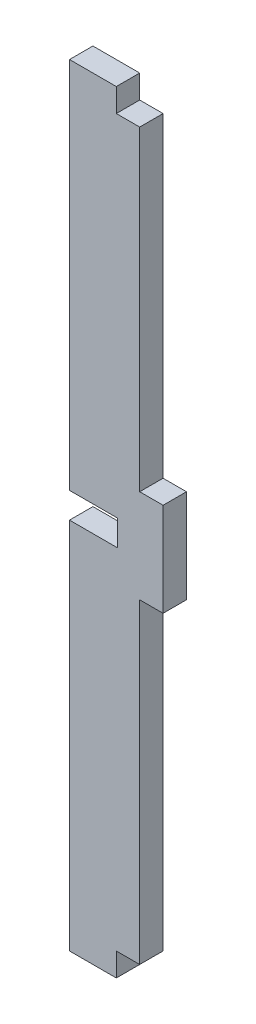
SolidWorks part; units mm, degrees
ref_plane "Front Plane" through (0, 0, 0) normal (0, 0, 1) x (1, 0, 0)
ref_plane "Top Plane" through (0, 0, 0) normal (0, 1, 0) x (1, 0, 0)
ref_plane "Right Plane" through (0, 0, 0) normal (1, 0, 0) x (0, 0, -1)
sketch "Model" plane through (0, 0, 0) normal (0, 0, 1) x (1, 0, 0)
  line L0 (-336.4543, -134.1912) -> (-336.4543, -213.9412)
  line L1 (-321.4543, -208.9412) -> (-321.4543, -141.4412)
  line L2 (-326.4543, -48.9412) -> (-336.4543, -48.9412)
  line L3 (-326.4543, -208.9412) -> (-321.4543, -208.9412)
  line L4 (-336.4543, -213.9412) -> (-326.4543, -213.9412)
  line L5 (-326.4543, -213.9412) -> (-326.4543, -208.9412)
  line L6 (-321.4543, -141.4412) -> (-316.4543, -141.4412)
  line L7 (-316.4543, -141.4412) -> (-316.4543, -121.4412)
  line L8 (-316.4543, -121.4412) -> (-321.4543, -121.4412)
  line L9 (-321.4543, -121.4412) -> (-321.4543, -53.9412)
  line L10 (-321.4543, -53.9412) -> (-326.4543, -53.9412)
  line L11 (-326.4543, -53.9412) -> (-326.4543, -48.9412)
  line L12 (-336.4543, -48.9412) -> (-336.4543, -128.6912)
  line L13 (-326.2043, -128.6912) -> (-336.4543, -128.6912)
  line L14 (-326.2043, -134.1912) -> (-326.2043, -128.6912)
  line L15 (-336.4543, -134.1912) -> (-326.2043, -134.1912)
  line L16 (-318.4543, -138.0497) -> (-320.6522, -138.0497)
  line L17 (-320.5835, -136.4747) -> (-320.4773, -136.1391)
  line L18 (-320.4773, -136.1391) -> (-320.3431, -135.9658)
  line L19 (-320.3431, -135.9658) -> (-320.1901, -135.9081)
  line L20 (-320.1901, -135.9081) -> (-318.9351, -135.9081)
  line L21 (-318.9351, -135.9081) -> (-318.8364, -135.9287)
  line L22 (-318.8364, -135.9287) -> (-318.7462, -135.9908)
  line L23 (-318.7462, -135.9908) -> (-318.5917, -136.239)
  line L24 (-318.5917, -136.239) -> (-318.4887, -136.5996)
  line L25 (-318.4887, -136.5996) -> (-318.4543, -137.032)
  line L26 (-318.4543, -137.032) -> (-318.4543, -138.0497)
  line L27 (-322.7623, -138.0497) -> (-318.4543, -138.0497)
  line L28 (-318.4543, -138.0497) -> (-318.4543, -137.032)
  line L29 (-318.4543, -137.032) -> (-318.4887, -136.5996)
  line L30 (-318.4887, -136.5996) -> (-318.5917, -136.239)
  line L31 (-318.5917, -136.239) -> (-318.7462, -135.9908)
  line L32 (-318.7462, -135.9908) -> (-318.8364, -135.9287)
  line L33 (-318.8364, -135.9287) -> (-318.9351, -135.9081)
  line L34 (-318.9351, -135.9081) -> (-320.19, -135.9081)
  line L35 (-320.19, -135.9081) -> (-320.3429, -135.9658)
  line L36 (-320.3429, -135.9658) -> (-320.4772, -136.1391)
  line L37 (-320.4772, -136.1391) -> (-320.5835, -136.4747)
  line L38 (-320.5835, -136.4747) -> (-320.6522, -137.032)
  line L39 (-320.716, -136.481) -> (-320.8206, -136.1391)
  line L40 (-320.8206, -136.1391) -> (-320.9595, -135.9658)
  line L41 (-320.9595, -135.9658) -> (-321.114, -135.9081)
  line L42 (-321.114, -135.9081) -> (-322.2815, -135.9081)
  line L43 (-322.2815, -135.9081) -> (-322.3752, -135.9287)
  line L44 (-322.3752, -135.9287) -> (-322.4626, -135.9908)
  line L45 (-322.4626, -135.9908) -> (-322.6187, -136.239)
  line L46 (-322.6187, -136.239) -> (-322.7264, -136.6027)
  line L47 (-322.7264, -136.6027) -> (-322.7623, -137.032)
  line L48 (-322.7623, -137.032) -> (-322.7623, -138.0497)
  line L49 (-320.6522, -137.032) -> (-320.6522, -138.0497)
  line L50 (-320.6522, -138.0497) -> (-322.7623, -138.0497)
  line L51 (-322.7623, -138.0497) -> (-322.7623, -137.032)
  line L52 (-322.7623, -137.032) -> (-322.7264, -136.6027)
  line L53 (-322.7264, -136.6027) -> (-322.6186, -136.239)
  line L54 (-322.6186, -136.239) -> (-322.4625, -135.9908)
  line L55 (-322.4625, -135.9908) -> (-322.3751, -135.9287)
  line L56 (-322.3751, -135.9287) -> (-322.2815, -135.9081)
  line L57 (-322.2815, -135.9081) -> (-321.1139, -135.9081)
  line L58 (-321.1139, -135.9081) -> (-320.9593, -135.9658)
  line L59 (-320.9593, -135.9658) -> (-320.8204, -136.1391)
  line L60 (-320.8204, -136.1391) -> (-320.716, -136.481)
  line L61 (-320.716, -136.481) -> (-320.6522, -137.032)
  line L62 (-322.7684, -133.9913) -> (-320.6518, -133.4396)
  line L63 (-322.7684, -133.9913) -> (-320.6519, -134.5121)
  line L64 (-320.2713, -133.3419) -> (-318.4543, -132.8674)
  line L65 (-318.4895, -131.3729) -> (-318.5948, -131.7343)
  line L66 (-318.5948, -131.7343) -> (-318.7501, -131.9754)
  line L67 (-318.7501, -131.9754) -> (-318.8389, -132.0357)
  line L68 (-318.8389, -132.0357) -> (-318.9351, -132.0558)
  line L69 (-318.9351, -132.0558) -> (-318.8389, -132.0357)
  line L70 (-318.8389, -132.0357) -> (-318.7501, -131.9754)
  line L71 (-318.7501, -131.9754) -> (-318.5948, -131.7343)
  line L72 (-318.5948, -131.7343) -> (-318.4895, -131.3729)
  line L73 (-318.4895, -130.4909) -> (-318.5948, -130.1296)
  line L74 (-318.5948, -130.1296) -> (-318.7501, -129.8884)
  line L75 (-318.7501, -129.8884) -> (-318.8389, -129.8281)
  line L76 (-318.8389, -129.8281) -> (-318.9351, -129.808)
  line L77 (-318.9351, -129.808) -> (-320.6457, -129.808)
  line L78 (-320.6457, -129.808) -> (-320.742, -129.8281)
  line L79 (-320.742, -129.8281) -> (-320.8307, -129.8884)
  line L80 (-320.8307, -129.8884) -> (-320.9861, -130.1296)
  line L81 (-320.9861, -130.1296) -> (-321.0914, -130.4909)
  line L82 (-321.0914, -130.4909) -> (-321.1265, -130.9319)
  line L83 (-321.1265, -130.9319) -> (-321.0266, -131.6063)
  line L84 (-321.0266, -131.6063) -> (-320.9002, -131.8373)
  line L85 (-320.9002, -131.8373) -> (-320.6457, -132.0558)
  line L86 (-320.6457, -132.0558) -> (-322.7623, -132.0558)
  line L87 (-322.7623, -132.0558) -> (-322.7623, -129.883)
  line L88 (-322.7623, -129.883) -> (-322.7623, -132.0558)
  line L89 (-322.7623, -132.0558) -> (-320.6457, -132.0558)
  line L90 (-320.6457, -132.0558) -> (-320.9002, -131.8373)
  line L91 (-320.9002, -131.8373) -> (-321.0266, -131.6063)
  line L92 (-321.0266, -131.6063) -> (-321.1265, -130.9319)
  line L93 (-321.1265, -130.9319) -> (-321.0914, -130.4909)
  line L94 (-321.0914, -130.4909) -> (-320.9861, -130.1296)
  line L95 (-320.9861, -130.1296) -> (-320.8307, -129.8884)
  line L96 (-320.8307, -129.8884) -> (-320.742, -129.8281)
  line L97 (-320.742, -129.8281) -> (-320.6457, -129.808)
  line L98 (-320.6457, -129.808) -> (-318.9351, -129.808)
  line L99 (-318.9351, -129.808) -> (-318.8389, -129.8281)
  line L100 (-318.8389, -129.8281) -> (-318.7501, -129.8884)
  line L101 (-318.7501, -129.8884) -> (-318.5948, -130.1296)
  line L102 (-318.5948, -130.1296) -> (-318.4895, -130.4909)
  line L103 (-318.4895, -130.4909) -> (-318.4543, -130.9319)
  line L104 (-318.4543, -130.9319) -> (-318.4895, -131.3729)
  line L105 (-320.6518, -133.4396) -> (-320.277, -133.3419)
  line L106 (-320.6519, -134.5121) -> (-318.4543, -135.0528)
  line L107 (-320.6519, -134.5121) -> (-320.6518, -133.4396)
  line L108 (-323.4543, -126.308) -> (-318.4543, -126.308)
  line L109 (-320.4543, -127.308) -> (-318.4543, -126.308)
  line L110 (-320.4543, -125.308) -> (-318.4543, -126.308)
  line L111 (-323.9543, -95.9329) -> (-323.9543, -79.4495)
  line L112 (-329.35, -93.8973) -> (-329.35, -95.9329)
  line L113 (-333.5702, -89.939) -> (-329.35, -89.939)
  line L114 (-325.5382, -91.815) -> (-325.7185, -91.6909)
  line L115 (-325.5382, -91.815) -> (-325.229, -92.3114)
  line L116 (-325.2291, -86.3175) -> (-325.5382, -85.8211)
  line L117 (-329.0004, -92.1116) -> (-329.2127, -92.7828)
  line L118 (-332.6087, -91.6495) -> (-330.2737, -91.6495)
  line L119 (-329.35, -95.9329) -> (-324.9543, -95.9329)
  line L120 (-325.2291, -86.3175) -> (-325.023, -87.0387)
  line L121 (-325.7185, -85.697) -> (-325.9159, -85.6556)
  line L122 (-333.4984, -93.0388) -> (-333.5702, -93.8973)
  line L123 (-325.9159, -91.6495) -> (-328.4259, -91.6495)
  line L124 (-328.4257, -85.6556) -> (-325.9159, -85.6556)
  line L125 (-324.9543, -93.8973) -> (-324.9543, -95.9329)
  line L126 (-328.7319, -91.7651) -> (-329.0004, -92.1116)
  line L127 (-329.2127, -92.7828) -> (-329.35, -93.8973)
  line L128 (-324.9543, -93.8973) -> (-325.023, -93.0326)
  line L129 (-328.7315, -85.7712) -> (-328.4257, -85.6556)
  line L130 (-329.6868, -92.1116) -> (-329.4776, -92.7953)
  line L131 (-325.023, -87.0387) -> (-324.9543, -87.9034)
  line L132 (-329.9643, -91.7651) -> (-330.2737, -91.6495)
  line L133 (-325.023, -93.0326) -> (-325.229, -92.3114)
  line L134 (-332.6087, -91.6495) -> (-332.796, -91.6909)
  line L135 (-332.9708, -91.815) -> (-333.2829, -92.3114)
  line L136 (-324.9543, -87.9034) -> (-324.9543, -89.939)
  line L137 (-325.5382, -85.8211) -> (-325.7185, -85.697)
  line L138 (-329.0004, -86.1177) -> (-329.2127, -86.7889)
  line L139 (-329.6868, -92.1116) -> (-329.9643, -91.7651)
  line L140 (-329.0004, -86.1177) -> (-328.7315, -85.7712)
  line L141 (-333.5702, -95.9329) -> (-333.5702, -93.8973)
  line L142 (-333.5702, -95.9329) -> (-329.35, -95.9329)
  line L143 (-333.4984, -93.0388) -> (-333.2829, -92.3114)
  line L144 (-332.9708, -91.815) -> (-332.796, -91.6909)
  line L145 (-328.4259, -91.6495) -> (-328.7319, -91.7651)
  line L146 (-325.7185, -91.6909) -> (-325.9159, -91.6495)
  line L147 (-329.35, -93.8973) -> (-329.4776, -92.7953)
  line L148 (-329.2127, -86.7889) -> (-329.35, -87.9034)
  line L149 (-333.5702, -83.9451) -> (-329.3372, -83.9451)
  line L150 (-330.2988, -81.6973) -> (-330.2285, -80.8153)
  line L151 (-329.3372, -79.4495) -> (-325.9158, -79.4495)
  line L152 (-329.3372, -79.4495) -> (-329.5296, -79.4896)
  line L153 (-324.9543, -81.6973) -> (-325.0246, -82.5792)
  line L154 (-329.5296, -79.4896) -> (-329.7072, -79.6102)
  line L155 (-333.5702, -83.9451) -> (-333.5702, -79.5993)
  line L156 (-333.5702, -87.9034) -> (-333.5702, -89.939)
  line L157 (-329.35, -87.9034) -> (-329.35, -89.939)
  line L158 (-329.7072, -79.6102) -> (-330.0178, -80.0926)
  line L159 (-330.2988, -81.6973) -> (-330.0989, -83.046)
  line L160 (-332.7959, -85.697) -> (-332.9708, -85.8211)
  line L161 (-329.3372, -83.9451) -> (-329.846, -83.508)
  line L162 (-330.2285, -80.8153) -> (-330.0178, -80.0926)
  line L163 (-325.2353, -83.302) -> (-325.5459, -83.7843)
  line L164 (-325.9158, -79.4495) -> (-325.7235, -79.4896)
  line L165 (-333.4984, -87.0449) -> (-333.5702, -87.9034)
  line L166 (-325.7235, -79.4896) -> (-325.5459, -79.6102)
  line L167 (-325.5459, -79.6102) -> (-325.2353, -80.0926)
  line L168 (-329.6868, -86.1177) -> (-329.4776, -86.8014)
  line L169 (-330.0989, -83.046) -> (-329.846, -83.508)
  line L170 (-325.2353, -83.302) -> (-325.0246, -82.5792)
  line L171 (-332.6087, -85.6556) -> (-330.2737, -85.6556)
  line L172 (-332.6087, -85.6556) -> (-332.7959, -85.697)
  line L173 (-333.283, -86.3175) -> (-332.9708, -85.8211)
  line L174 (-330.2737, -85.6556) -> (-329.9643, -85.7712)
  line L175 (-329.4776, -86.8014) -> (-329.35, -87.9034)
  line L176 (-329.6868, -86.1177) -> (-329.9643, -85.7712)
  line L177 (-333.4984, -87.0449) -> (-333.283, -86.3175)
  line L178 (-325.9158, -83.9451) -> (-325.7235, -83.9049)
  line L179 (-325.7235, -83.9049) -> (-325.5459, -83.7843)
  line L180 (-325.2353, -80.0926) -> (-325.0246, -80.8153)
  line L181 (-325.0246, -80.8153) -> (-324.9543, -81.6973)
  line L182 (-329.35, -89.939) -> (-324.9543, -89.939)
  line L183 (-328.4543, -61.1859) -> (-330.6522, -61.1859)
  line L184 (-330.6522, -61.1859) -> (-330.6522, -60.1682)
  line L185 (-330.6522, -60.1682) -> (-330.5835, -59.6109)
  line L186 (-330.5835, -59.6109) -> (-330.4773, -59.2753)
  line L187 (-330.4773, -59.2753) -> (-330.3431, -59.102)
  line L188 (-330.3431, -59.102) -> (-330.1901, -59.0443)
  line L189 (-330.1901, -59.0443) -> (-328.9351, -59.0443)
  line L190 (-328.9351, -59.0443) -> (-328.8364, -59.0649)
  line L191 (-328.8364, -59.0649) -> (-328.7462, -59.127)
  line L192 (-328.7462, -59.127) -> (-328.5917, -59.3752)
  line L193 (-328.5917, -59.3752) -> (-328.4887, -59.7358)
  line L194 (-328.4887, -59.7358) -> (-328.4543, -60.1682)
  line L195 (-328.4543, -60.1682) -> (-328.4543, -61.1859)
  line L196 (-332.7623, -61.1859) -> (-328.4543, -61.1859)
  line L197 (-328.4543, -61.1859) -> (-328.4543, -60.1682)
  line L198 (-328.4543, -60.1682) -> (-328.4887, -59.7358)
  line L199 (-328.4887, -59.7358) -> (-328.5917, -59.3752)
  line L200 (-328.5917, -59.3752) -> (-328.7462, -59.127)
  line L201 (-328.7462, -59.127) -> (-328.8364, -59.0649)
  line L202 (-328.8364, -59.0649) -> (-328.9351, -59.0443)
  line L203 (-328.9351, -59.0443) -> (-330.19, -59.0443)
  line L204 (-330.19, -59.0443) -> (-330.3429, -59.102)
  line L205 (-330.3429, -59.102) -> (-330.4772, -59.2753)
  line L206 (-330.4772, -59.2753) -> (-330.5833, -59.6109)
  line L207 (-330.5833, -59.6109) -> (-330.652, -60.1682)
  line L208 (-330.652, -60.1682) -> (-330.716, -59.6172)
  line L209 (-330.716, -59.6172) -> (-330.8206, -59.2753)
  line L210 (-330.8206, -59.2753) -> (-330.9595, -59.102)
  line L211 (-330.9595, -59.102) -> (-331.114, -59.0443)
  line L212 (-331.114, -59.0443) -> (-332.2815, -59.0443)
  line L213 (-332.2815, -59.0443) -> (-332.3752, -59.0649)
  line L214 (-332.3752, -59.0649) -> (-332.4626, -59.127)
  line L215 (-332.4626, -59.127) -> (-332.6187, -59.3752)
  line L216 (-332.6187, -59.3752) -> (-332.7264, -59.7389)
  line L217 (-332.7264, -59.7389) -> (-332.7623, -60.1682)
  line L218 (-332.7623, -60.1682) -> (-332.7623, -61.1859)
  line L219 (-330.6518, -60.1682) -> (-330.6518, -61.1859)
  line L220 (-330.6518, -61.1859) -> (-332.7623, -61.1859)
  line L221 (-332.7623, -61.1859) -> (-332.7623, -60.1682)
  line L222 (-332.7623, -60.1682) -> (-332.7264, -59.7389)
  line L223 (-332.7264, -59.7389) -> (-332.6186, -59.3752)
  line L224 (-332.6186, -59.3752) -> (-332.4625, -59.127)
  line L225 (-332.4625, -59.127) -> (-332.3751, -59.0649)
  line L226 (-332.3751, -59.0649) -> (-332.2815, -59.0443)
  line L227 (-332.2815, -59.0443) -> (-331.1139, -59.0443)
  line L228 (-331.1139, -59.0443) -> (-330.9593, -59.102)
  line L229 (-330.9593, -59.102) -> (-330.8204, -59.2753)
  line L230 (-330.8204, -59.2753) -> (-330.7158, -59.6172)
  line L231 (-330.7158, -59.6172) -> (-330.6518, -60.1682)
  line L232 (-332.7684, -58.189) -> (-328.4543, -58.189)
  line L233 (-328.4543, -56.0651) -> (-328.4895, -56.5061)
  line L234 (-328.4895, -56.5061) -> (-328.5948, -56.8674)
  line L235 (-328.5948, -56.8674) -> (-328.7501, -57.1086)
  line L236 (-328.7501, -57.1086) -> (-328.8389, -57.1689)
  line L237 (-328.8389, -57.1689) -> (-328.9351, -57.189)
  line L238 (-328.9351, -57.189) -> (-328.8389, -57.1689)
  line L239 (-328.8389, -57.1689) -> (-328.7501, -57.1086)
  line L240 (-328.7501, -57.1086) -> (-328.5948, -56.8674)
  line L241 (-328.5948, -56.8674) -> (-328.4895, -56.5061)
  line L242 (-328.4895, -55.6241) -> (-328.5948, -55.2627)
  line L243 (-328.5948, -55.2627) -> (-328.7501, -55.0216)
  line L244 (-328.7501, -55.0216) -> (-328.8389, -54.9613)
  line L245 (-328.8389, -54.9613) -> (-328.9351, -54.9412)
  line L246 (-328.9351, -54.9412) -> (-330.6457, -54.9412)
  line L247 (-330.6457, -54.9412) -> (-330.742, -54.9613)
  line L248 (-330.742, -54.9613) -> (-330.8307, -55.0216)
  line L249 (-330.8307, -55.0216) -> (-330.9861, -55.2627)
  line L250 (-330.9861, -55.2627) -> (-331.0914, -55.6241)
  line L251 (-331.0914, -55.6241) -> (-331.1265, -56.0651)
  line L252 (-331.1265, -56.0651) -> (-331.0266, -56.7394)
  line L253 (-331.0266, -56.7394) -> (-330.9002, -56.9705)
  line L254 (-330.9002, -56.9705) -> (-330.6457, -57.189)
  line L255 (-330.6457, -57.189) -> (-332.7623, -57.189)
  line L256 (-332.7623, -57.189) -> (-332.7623, -55.0161)
  line L257 (-332.7623, -55.0161) -> (-332.7623, -57.189)
  line L258 (-332.7623, -57.189) -> (-330.6457, -57.189)
  line L259 (-330.6457, -57.189) -> (-330.9002, -56.9705)
  line L260 (-330.9002, -56.9705) -> (-331.0266, -56.7394)
  line L261 (-331.0266, -56.7394) -> (-331.1265, -56.0651)
  line L262 (-331.1265, -56.0651) -> (-331.0914, -55.6241)
  line L263 (-331.0914, -55.6241) -> (-330.9861, -55.2627)
  line L264 (-330.9861, -55.2627) -> (-330.8307, -55.0216)
  line L265 (-330.8307, -55.0216) -> (-330.742, -54.9613)
  line L266 (-330.742, -54.9613) -> (-330.6457, -54.9412)
  line L267 (-330.6457, -54.9412) -> (-328.9351, -54.9412)
  line L268 (-328.9351, -54.9412) -> (-328.8389, -54.9613)
  line L269 (-328.8389, -54.9613) -> (-328.7501, -55.0216)
  line L270 (-328.7501, -55.0216) -> (-328.5948, -55.2627)
  line L271 (-328.5948, -55.2627) -> (-328.4895, -55.6241)
  line L272 (-328.4895, -55.6241) -> (-328.4543, -56.0651)
  line L273 (-333.4543, -51.4412) -> (-328.4543, -51.4412)
  line L274 (-330.4543, -52.4412) -> (-328.4543, -51.4412)
  line L275 (-330.4543, -50.4412) -> (-328.4543, -51.4412)
  line L276 (-329.1319, -151.9268) -> (-331.3297, -151.9268)
  line L277 (-331.3297, -151.9268) -> (-331.3297, -150.909)
  line L278 (-331.3297, -150.909) -> (-331.2611, -150.3518)
  line L279 (-331.2611, -150.3518) -> (-331.1549, -150.0161)
  line L280 (-331.1549, -150.0161) -> (-331.0207, -149.8429)
  line L281 (-331.0207, -149.8429) -> (-330.8677, -149.7851)
  line L282 (-330.8677, -149.7851) -> (-329.6127, -149.7851)
  line L283 (-329.6127, -149.7851) -> (-329.5139, -149.8058)
  line L284 (-329.5139, -149.8058) -> (-329.4238, -149.8678)
  line L285 (-329.4238, -149.8678) -> (-329.2693, -150.116)
  line L286 (-329.2693, -150.116) -> (-329.1662, -150.4766)
  line L287 (-329.1662, -150.4766) -> (-329.1319, -150.909)
  line L288 (-329.1319, -150.909) -> (-329.1319, -151.9268)
  line L289 (-333.4398, -151.9268) -> (-329.1319, -151.9268)
  line L290 (-329.1319, -151.9268) -> (-329.1319, -150.909)
  line L291 (-329.1319, -150.909) -> (-329.1662, -150.4766)
  line L292 (-329.1662, -150.4766) -> (-329.2692, -150.116)
  line L293 (-329.2692, -150.116) -> (-329.4238, -149.8678)
  line L294 (-329.4238, -149.8678) -> (-329.5139, -149.8058)
  line L295 (-329.5139, -149.8058) -> (-329.6126, -149.7851)
  line L296 (-329.6126, -149.7851) -> (-330.8675, -149.7851)
  line L297 (-330.8675, -149.7851) -> (-331.0205, -149.8429)
  line L298 (-331.0205, -149.8429) -> (-331.1547, -150.0161)
  line L299 (-331.1547, -150.0161) -> (-331.2609, -150.3518)
  line L300 (-331.2609, -150.3518) -> (-331.3295, -150.909)
  line L301 (-331.3295, -150.909) -> (-331.3935, -150.358)
  line L302 (-331.3935, -150.358) -> (-331.4981, -150.0161)
  line L303 (-331.4981, -150.0161) -> (-331.637, -149.8429)
  line L304 (-331.637, -149.8429) -> (-331.7916, -149.7851)
  line L305 (-331.7916, -149.7851) -> (-332.9591, -149.7851)
  line L306 (-332.9591, -149.7851) -> (-333.0527, -149.8058)
  line L307 (-333.0527, -149.8058) -> (-333.1401, -149.8678)
  line L308 (-333.1401, -149.8678) -> (-333.2962, -150.116)
  line L309 (-333.2962, -150.116) -> (-333.4039, -150.4798)
  line L310 (-333.4039, -150.4798) -> (-333.4398, -150.909)
  line L311 (-333.4398, -150.909) -> (-333.4398, -151.9268)
  line L312 (-331.3293, -150.909) -> (-331.3293, -151.9268)
  line L313 (-331.3293, -151.9268) -> (-333.4398, -151.9268)
  line L314 (-333.4398, -151.9268) -> (-333.4398, -150.909)
  line L315 (-333.4398, -150.909) -> (-333.4039, -150.4798)
  line L316 (-333.4039, -150.4798) -> (-333.2962, -150.116)
  line L317 (-333.2962, -150.116) -> (-333.1401, -149.8678)
  line L318 (-333.1401, -149.8678) -> (-333.0527, -149.8058)
  line L319 (-333.0527, -149.8058) -> (-332.959, -149.7851)
  line L320 (-332.959, -149.7851) -> (-331.7914, -149.7851)
  line L321 (-331.7914, -149.7851) -> (-331.6369, -149.8429)
  line L322 (-331.6369, -149.8429) -> (-331.4979, -150.0161)
  line L323 (-331.4979, -150.0161) -> (-331.3934, -150.358)
  line L324 (-331.3934, -150.358) -> (-331.3293, -150.909)
  line L325 (-329.9186, -146.682) -> (-329.6126, -146.682)
  line L326 (-329.6126, -146.682) -> (-329.5163, -146.7023)
  line L327 (-329.5163, -146.7023) -> (-329.4269, -146.7632)
  line L328 (-329.4269, -146.7632) -> (-329.2692, -147.0067)
  line L329 (-329.2692, -147.0067) -> (-329.1662, -147.3626)
  line L330 (-329.1662, -147.3626) -> (-329.1319, -147.8059)
  line L331 (-329.1319, -147.8059) -> (-329.1662, -148.2508)
  line L332 (-329.1662, -148.2508) -> (-329.2692, -148.6114)
  line L333 (-329.2692, -148.6114) -> (-329.4238, -148.8502)
  line L334 (-329.4238, -148.8502) -> (-329.5139, -148.9099)
  line L335 (-329.5139, -148.9099) -> (-329.6126, -148.9298)
  line L336 (-329.6126, -148.9298) -> (-332.9591, -148.9298)
  line L337 (-332.9591, -148.9298) -> (-333.0551, -148.9099)
  line L338 (-333.0551, -148.9099) -> (-333.1432, -148.8502)
  line L339 (-333.1432, -148.8502) -> (-333.2962, -148.6114)
  line L340 (-333.2962, -148.6114) -> (-333.4039, -148.2446)
  line L341 (-333.4039, -148.2446) -> (-333.4398, -147.8059)
  line L342 (-333.4398, -147.8059) -> (-333.4039, -147.372)
  line L343 (-333.4039, -147.372) -> (-333.2962, -147.0067)
  line L344 (-333.2962, -147.0067) -> (-333.1401, -146.7632)
  line L345 (-333.1401, -146.7632) -> (-333.0527, -146.7023)
  line L346 (-333.0527, -146.7023) -> (-332.9591, -146.682)
  line L347 (-332.9591, -146.682) -> (-332.6531, -146.682)
  line L348 (-332.6531, -146.682) -> (-332.9591, -146.682)
  line L349 (-332.9591, -146.682) -> (-333.0527, -146.7023)
  line L350 (-333.0527, -146.7023) -> (-333.1401, -146.7632)
  line L351 (-333.1401, -146.7632) -> (-333.2962, -147.0067)
  line L352 (-333.2962, -147.0067) -> (-333.4039, -147.372)
  line L353 (-333.4039, -147.372) -> (-333.4398, -147.8059)
  line L354 (-333.4398, -147.8059) -> (-333.4039, -148.2446)
  line L355 (-333.4039, -148.2446) -> (-333.2962, -148.6114)
  line L356 (-333.2962, -148.6114) -> (-333.1432, -148.8502)
  line L357 (-333.1432, -148.8502) -> (-333.0551, -148.9099)
  line L358 (-333.0551, -148.9099) -> (-332.9591, -148.9298)
  line L359 (-332.9591, -148.9298) -> (-329.6126, -148.9298)
  line L360 (-329.6126, -148.9298) -> (-329.5139, -148.9099)
  line L361 (-329.5139, -148.9099) -> (-329.4238, -148.8502)
  line L362 (-329.4238, -148.8502) -> (-329.2692, -148.6114)
  line L363 (-329.2692, -148.6114) -> (-329.1662, -148.2508)
  line L364 (-329.1662, -148.2508) -> (-329.1319, -147.8059)
  line L365 (-329.1319, -147.8059) -> (-329.1662, -147.3626)
  line L366 (-329.1662, -147.3626) -> (-329.2692, -147.0067)
  line L367 (-329.2692, -147.0067) -> (-329.4269, -146.7632)
  line L368 (-329.4269, -146.7632) -> (-329.5163, -146.7023)
  line L369 (-329.5163, -146.7023) -> (-329.6126, -146.682)
  line L370 (-329.6126, -146.682) -> (-329.9186, -146.682)
  line L371 (-329.1319, -144.8151) -> (-329.167, -145.2561)
  line L372 (-329.167, -145.2561) -> (-329.2724, -145.6174)
  line L373 (-329.2724, -145.6174) -> (-329.4277, -145.8586)
  line L374 (-329.4277, -145.8586) -> (-329.5165, -145.9189)
  line L375 (-329.5165, -145.9189) -> (-329.6126, -145.939)
  line L376 (-329.6126, -145.939) -> (-329.5165, -145.9189)
  line L377 (-329.5165, -145.9189) -> (-329.4277, -145.8586)
  line L378 (-329.4277, -145.8586) -> (-329.2724, -145.6174)
  line L379 (-329.2724, -145.6174) -> (-329.167, -145.2561)
  line L380 (-329.167, -144.3741) -> (-329.2724, -144.0127)
  line L381 (-329.2724, -144.0127) -> (-329.4277, -143.7716)
  line L382 (-329.4277, -143.7716) -> (-329.5165, -143.7113)
  line L383 (-329.5165, -143.7113) -> (-329.6126, -143.6912)
  line L384 (-329.6126, -143.6912) -> (-331.3233, -143.6912)
  line L385 (-331.3233, -143.6912) -> (-331.4195, -143.7113)
  line L386 (-331.4195, -143.7113) -> (-331.5083, -143.7716)
  line L387 (-331.5083, -143.7716) -> (-331.6636, -144.0127)
  line L388 (-331.6636, -144.0127) -> (-331.769, -144.3741)
  line L389 (-331.769, -144.3741) -> (-331.8041, -144.8151)
  line L390 (-331.8041, -144.8151) -> (-331.7042, -145.4894)
  line L391 (-331.7042, -145.4894) -> (-331.5777, -145.7205)
  line L392 (-331.5777, -145.7205) -> (-331.3233, -145.939)
  line L393 (-331.3233, -145.939) -> (-333.4398, -145.939)
  line L394 (-333.4398, -145.939) -> (-333.4398, -143.7661)
  line L395 (-333.4398, -143.7661) -> (-333.4398, -145.939)
  line L396 (-333.4398, -145.939) -> (-331.3233, -145.939)
  line L397 (-331.3233, -145.939) -> (-331.5777, -145.7205)
  line L398 (-331.5777, -145.7205) -> (-331.7042, -145.4894)
  line L399 (-331.7042, -145.4894) -> (-331.8041, -144.8151)
  line L400 (-331.8041, -144.8151) -> (-331.769, -144.3741)
  line L401 (-331.769, -144.3741) -> (-331.6636, -144.0127)
  line L402 (-331.6636, -144.0127) -> (-331.5083, -143.7716)
  line L403 (-331.5083, -143.7716) -> (-331.4195, -143.7113)
  line L404 (-331.4195, -143.7113) -> (-331.3233, -143.6912)
  line L405 (-331.3233, -143.6912) -> (-329.6126, -143.6912)
  line L406 (-329.6126, -143.6912) -> (-329.5165, -143.7113)
  line L407 (-329.5165, -143.7113) -> (-329.4277, -143.7716)
  line L408 (-329.4277, -143.7716) -> (-329.2724, -144.0127)
  line L409 (-329.2724, -144.0127) -> (-329.167, -144.3741)
  line L410 (-329.167, -144.3741) -> (-329.1319, -144.8151)
  line L411 (-331.3293, -141.1912) -> (-331.3293, -136.1912)
  line L412 (-330.3293, -138.1912) -> (-331.3293, -136.1912)
  line L413 (-332.3293, -138.1912) -> (-331.3293, -136.1912)
  line L414 (-328.4543, -207.9412) -> (-330.6522, -207.9412)
  line L415 (-330.6522, -207.9412) -> (-330.6522, -206.9234)
  line L416 (-330.6522, -206.9234) -> (-330.5835, -206.3662)
  line L417 (-330.5835, -206.3662) -> (-330.4773, -206.0305)
  line L418 (-330.4773, -206.0305) -> (-330.3431, -205.8573)
  line L419 (-330.3431, -205.8573) -> (-330.1901, -205.7995)
  line L420 (-330.1901, -205.7995) -> (-328.9351, -205.7995)
  line L421 (-328.9351, -205.7995) -> (-328.8364, -205.8202)
  line L422 (-328.8364, -205.8202) -> (-328.7462, -205.8822)
  line L423 (-328.7462, -205.8822) -> (-328.5917, -206.1304)
  line L424 (-328.5917, -206.1304) -> (-328.4887, -206.491)
  line L425 (-328.4887, -206.491) -> (-328.4543, -206.9234)
  line L426 (-328.4543, -206.9234) -> (-328.4543, -207.9412)
  line L427 (-332.7623, -207.9412) -> (-328.4543, -207.9412)
  line L428 (-328.4543, -207.9412) -> (-328.4543, -206.9234)
  line L429 (-328.4543, -206.9234) -> (-328.4887, -206.491)
  line L430 (-328.4887, -206.491) -> (-328.5917, -206.1304)
  line L431 (-328.5917, -206.1304) -> (-328.7462, -205.8822)
  line L432 (-328.7462, -205.8822) -> (-328.8364, -205.8202)
  line L433 (-328.8364, -205.8202) -> (-328.9351, -205.7995)
  line L434 (-328.9351, -205.7995) -> (-330.19, -205.7995)
  line L435 (-330.19, -205.7995) -> (-330.3429, -205.8573)
  line L436 (-330.3429, -205.8573) -> (-330.4772, -206.0305)
  line L437 (-330.4772, -206.0305) -> (-330.5833, -206.3662)
  line L438 (-330.5833, -206.3662) -> (-330.652, -206.9234)
  line L439 (-330.652, -206.9234) -> (-330.716, -206.3724)
  line L440 (-330.716, -206.3724) -> (-330.8206, -206.0305)
  line L441 (-330.8206, -206.0305) -> (-330.9595, -205.8573)
  line L442 (-330.9595, -205.8573) -> (-331.114, -205.7995)
  line L443 (-331.114, -205.7995) -> (-332.2815, -205.7995)
  line L444 (-332.2815, -205.7995) -> (-332.3752, -205.8202)
  line L445 (-332.3752, -205.8202) -> (-332.4626, -205.8822)
  line L446 (-332.4626, -205.8822) -> (-332.6187, -206.1304)
  line L447 (-332.6187, -206.1304) -> (-332.7264, -206.4941)
  line L448 (-332.7264, -206.4941) -> (-332.7623, -206.9234)
  line L449 (-332.7623, -206.9234) -> (-332.7623, -207.9412)
  line L450 (-330.6518, -206.9234) -> (-330.6518, -207.9412)
  line L451 (-330.6518, -207.9412) -> (-332.7623, -207.9412)
  line L452 (-332.7623, -207.9412) -> (-332.7623, -206.9234)
  line L453 (-332.7623, -206.9234) -> (-332.7264, -206.4941)
  line L454 (-332.7264, -206.4941) -> (-332.6186, -206.1304)
  line L455 (-332.6186, -206.1304) -> (-332.4625, -205.8822)
  line L456 (-332.4625, -205.8822) -> (-332.3751, -205.8202)
  line L457 (-332.3751, -205.8202) -> (-332.2815, -205.7995)
  line L458 (-332.2815, -205.7995) -> (-331.1139, -205.7995)
  line L459 (-331.1139, -205.7995) -> (-330.9593, -205.8573)
  line L460 (-330.9593, -205.8573) -> (-330.8204, -206.0305)
  line L461 (-330.8204, -206.0305) -> (-330.7158, -206.3724)
  line L462 (-330.7158, -206.3724) -> (-330.6518, -206.9234)
  line L463 (-328.9351, -202.6964) -> (-328.8389, -202.7165)
  line L464 (-328.8389, -202.7165) -> (-328.7501, -202.7768)
  line L465 (-328.7501, -202.7768) -> (-328.5948, -203.018)
  line L466 (-328.5948, -203.018) -> (-328.4895, -203.3793)
  line L467 (-328.4895, -203.3793) -> (-328.4543, -203.8203)
  line L468 (-328.4543, -203.8203) -> (-328.4895, -204.2613)
  line L469 (-328.4895, -204.2613) -> (-328.5948, -204.6227)
  line L470 (-328.5948, -204.6227) -> (-328.7501, -204.8638)
  line L471 (-328.7501, -204.8638) -> (-328.8389, -204.9241)
  line L472 (-328.8389, -204.9241) -> (-328.9351, -204.9442)
  line L473 (-328.9351, -204.9442) -> (-332.2815, -204.9442)
  line L474 (-332.2815, -204.9442) -> (-332.3777, -204.9241)
  line L475 (-332.3777, -204.9241) -> (-332.4665, -204.8638)
  line L476 (-332.4665, -204.8638) -> (-332.6218, -204.6227)
  line L477 (-332.6218, -204.6227) -> (-332.7271, -204.2613)
  line L478 (-332.7271, -204.2613) -> (-332.7623, -203.8203)
  line L479 (-332.7623, -203.8203) -> (-332.7271, -203.3793)
  line L480 (-332.7271, -203.3793) -> (-332.6218, -203.018)
  line L481 (-332.6218, -203.018) -> (-332.4665, -202.7768)
  line L482 (-332.4665, -202.7768) -> (-332.3777, -202.7165)
  line L483 (-332.3777, -202.7165) -> (-332.2815, -202.6964)
  line L484 (-332.2815, -202.6964) -> (-331.9756, -202.6964)
  line L485 (-331.9756, -202.6964) -> (-332.2815, -202.6964)
  line L486 (-332.2815, -202.6964) -> (-332.3777, -202.7165)
  line L487 (-332.3777, -202.7165) -> (-332.4665, -202.7768)
  line L488 (-332.4665, -202.7768) -> (-332.6218, -203.018)
  line L489 (-332.6218, -203.018) -> (-332.7271, -203.3793)
  line L490 (-332.7271, -203.3793) -> (-332.7623, -203.8203)
  line L491 (-332.7623, -203.8203) -> (-332.7271, -204.2613)
  line L492 (-332.7271, -204.2613) -> (-332.6218, -204.6227)
  line L493 (-332.6218, -204.6227) -> (-332.4665, -204.8638)
  line L494 (-332.4665, -204.8638) -> (-332.3777, -204.9241)
  line L495 (-332.3777, -204.9241) -> (-332.2815, -204.9442)
  line L496 (-332.2815, -204.9442) -> (-328.9351, -204.9442)
  line L497 (-328.9351, -204.9442) -> (-328.8389, -204.9241)
  line L498 (-328.8389, -204.9241) -> (-328.7501, -204.8638)
  line L499 (-328.7501, -204.8638) -> (-328.5948, -204.6227)
  line L500 (-328.5948, -204.6227) -> (-328.4895, -204.2613)
  line L501 (-328.4895, -204.2613) -> (-328.4543, -203.8203)
  line L502 (-328.4543, -203.8203) -> (-328.4895, -203.3793)
  line L503 (-328.4895, -203.3793) -> (-328.5948, -203.018)
  line L504 (-328.5948, -203.018) -> (-328.7501, -202.7768)
  line L505 (-328.7501, -202.7768) -> (-328.8389, -202.7165)
  line L506 (-330.6083, -202.6964) -> (-330.6083, -203.8078)
  line L507 (-330.6083, -203.8078) -> (-330.6083, -202.6964)
  line L508 (-330.6083, -202.6964) -> (-328.9351, -202.6964)
  line L509 (-328.4543, -200.8234) -> (-328.4895, -201.2643)
  line L510 (-328.4895, -201.2643) -> (-328.5948, -201.6257)
  line L511 (-328.5948, -201.6257) -> (-328.7501, -201.8669)
  line L512 (-328.7501, -201.8669) -> (-328.8389, -201.9272)
  line L513 (-328.8389, -201.9272) -> (-328.9351, -201.9473)
  line L514 (-328.9351, -201.9473) -> (-328.8389, -201.9272)
  line L515 (-328.8389, -201.9272) -> (-328.7501, -201.8669)
  line L516 (-328.7501, -201.8669) -> (-328.5948, -201.6257)
  line L517 (-328.5948, -201.6257) -> (-328.4895, -201.2643)
  line L518 (-328.4895, -200.3824) -> (-328.5948, -200.021)
  line L519 (-328.5948, -200.021) -> (-328.7501, -199.7798)
  line L520 (-328.7501, -199.7798) -> (-328.8389, -199.7196)
  line L521 (-328.8389, -199.7196) -> (-328.9351, -199.6995)
  line L522 (-328.9351, -199.6995) -> (-330.6457, -199.6995)
  line L523 (-330.6457, -199.6995) -> (-330.742, -199.7196)
  line L524 (-330.742, -199.7196) -> (-330.8307, -199.7798)
  line L525 (-330.8307, -199.7798) -> (-330.9861, -200.021)
  line L526 (-330.9861, -200.021) -> (-331.0914, -200.3824)
  line L527 (-331.0914, -200.3824) -> (-331.1265, -200.8234)
  line L528 (-331.1265, -200.8234) -> (-331.0266, -201.4977)
  line L529 (-331.0266, -201.4977) -> (-330.9002, -201.7287)
  line L530 (-330.9002, -201.7287) -> (-330.6457, -201.9473)
  line L531 (-330.6457, -201.9473) -> (-332.7623, -201.9473)
  line L532 (-332.7623, -201.9473) -> (-332.7623, -199.7744)
  line L533 (-332.7623, -199.7744) -> (-332.7623, -201.9473)
  line L534 (-332.7623, -201.9473) -> (-330.6457, -201.9473)
  line L535 (-330.6457, -201.9473) -> (-330.9002, -201.7287)
  line L536 (-330.9002, -201.7287) -> (-331.0266, -201.4977)
  line L537 (-331.0266, -201.4977) -> (-331.1265, -200.8234)
  line L538 (-331.1265, -200.8234) -> (-331.0914, -200.3824)
  line L539 (-331.0914, -200.3824) -> (-330.9861, -200.021)
  line L540 (-330.9861, -200.021) -> (-330.8307, -199.7798)
  line L541 (-330.8307, -199.7798) -> (-330.742, -199.7196)
  line L542 (-330.742, -199.7196) -> (-330.6457, -199.6995)
  line L543 (-330.6457, -199.6995) -> (-328.9351, -199.6995)
  line L544 (-328.9351, -199.6995) -> (-328.8389, -199.7196)
  line L545 (-328.8389, -199.7196) -> (-328.7501, -199.7798)
  line L546 (-328.7501, -199.7798) -> (-328.5948, -200.021)
  line L547 (-328.5948, -200.021) -> (-328.4895, -200.3824)
  line L548 (-328.4895, -200.3824) -> (-328.4543, -200.8234)
  line L549 (-333.4543, -211.4412) -> (-328.4543, -211.4412)
  line L550 (-330.4543, -212.4412) -> (-328.4543, -211.4412)
  line L551 (-330.4543, -210.4412) -> (-328.4543, -211.4412)
sketch "Sketch2" plane through (0, 0, 0) normal (0, 0, 1) x (1, 0, 0)
  line L0 (-326.4543, -53.9412) -> (-326.4543, -48.9412) construction
  line L1 (-321.4543, -53.9412) -> (-326.4543, -53.9412) construction
  line L2 (-321.4543, -121.4412) -> (-321.4543, -53.9412) construction
  line L3 (-316.4543, -121.4412) -> (-321.4543, -121.4412) construction
  line L4 (-316.4543, -141.4412) -> (-316.4543, -121.4412) construction
  line L5 (-321.4543, -141.4412) -> (-316.4543, -141.4412) construction
  line L6 (-321.4543, -208.9412) -> (-321.4543, -141.4412) construction
  line L7 (-326.4543, -208.9412) -> (-321.4543, -208.9412) construction
  line L8 (-326.4543, -213.9412) -> (-326.4543, -208.9412) construction
  line L9 (-336.4543, -213.9412) -> (-326.4543, -213.9412) construction
  line L10 (-336.4543, -134.1912) -> (-336.4543, -213.9412) construction
  line L11 (-336.4543, -134.1912) -> (-326.2043, -134.1912) construction
  line L12 (-326.2043, -134.1912) -> (-326.2043, -128.6912) construction
  line L13 (-326.2043, -128.6912) -> (-336.4543, -128.6912) construction
  line L14 (-336.4543, -48.9412) -> (-336.4543, -128.6912) construction
  line L15 (-326.4543, -48.9412) -> (-336.4543, -48.9412) construction
  line L16 (-326.4543, -53.9412) -> (-326.4543, -48.9412)
  line L17 (-321.4543, -53.9412) -> (-326.4543, -53.9412)
  line L18 (-321.4543, -121.4412) -> (-321.4543, -53.9412)
  line L19 (-316.4543, -121.4412) -> (-321.4543, -121.4412)
  line L20 (-316.4543, -141.4412) -> (-316.4543, -121.4412)
  line L21 (-321.4543, -141.4412) -> (-316.4543, -141.4412)
  line L22 (-321.4543, -208.9412) -> (-321.4543, -141.4412)
  line L23 (-326.4543, -208.9412) -> (-321.4543, -208.9412)
  line L24 (-326.4543, -213.9412) -> (-326.4543, -208.9412)
  line L25 (-336.4543, -213.9412) -> (-326.4543, -213.9412)
  line L26 (-336.4543, -134.1912) -> (-336.4543, -213.9412)
  line L27 (-336.4543, -134.1912) -> (-326.2043, -134.1912)
  line L28 (-326.2043, -134.1912) -> (-326.2043, -128.6912)
  line L29 (-326.2043, -128.6912) -> (-336.4543, -128.6912)
  line L30 (-336.4543, -48.9412) -> (-336.4543, -128.6912)
  line L31 (-326.4543, -48.9412) -> (-336.4543, -48.9412)
extrude "Boss-Extrude1" add sketch "Sketch2" along normal mid plane 5
